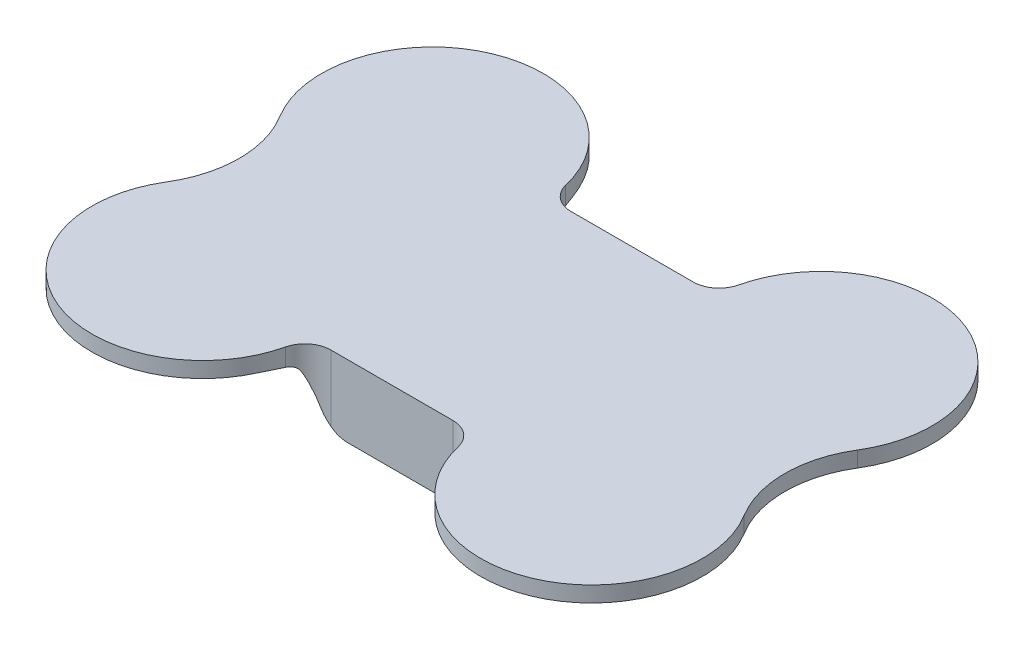
SolidWorks part; units mm, degrees
material "P-FIlament 721"
ref_plane "Front Plane" through (0, 0, 0) normal (0, 0, 1) x (1, 0, 0)
ref_plane "Top Plane" through (0, 0, 0) normal (0, 1, 0) x (1, 0, 0)
ref_plane "Right Plane" through (0, 0, 0) normal (1, 0, 0) x (0, 0, -1)
sketch "Sketch2" plane through (0, 0, 0) normal (0, 1, 0) x (1, 0, 0)
  line L4 (-23.3898, -46) -> (23.3898, -46)
  line L5 (-23.3898, 46) -> (23.3898, 46)
  arc A12 (-33.1251, 53.7143) -> (-110.703, 21.7381) centre (-74.5, 44) ccw
  arc A13 (-110.703, -21.7381) -> (-33.1251, -53.7143) centre (-74.5, -44) ccw
  arc A14 (33.1251, -53.7143) -> (110.703, -21.7381) centre (74.5, -44) ccw
  arc A15 (110.703, 21.7381) -> (33.1251, 53.7143) centre (74.5, 44) ccw
  arc A16 (-23.3898, 46) -> (-33.1251, 53.7143) centre (-23.3898, 56) cw
  arc A17 (33.1251, 53.7143) -> (23.3898, 46) centre (23.3898, 56) cw
  arc A18 (23.3898, -46) -> (33.1251, -53.7143) centre (23.3898, -56) cw
  arc A19 (-23.3898, -46) -> (-33.1251, -53.7143) centre (-23.3898, -56) ccw
  arc A20 (-110.703, -21.7381) -> (-110.703, 21.7381) centre (-146.0542, 0) ccw
  arc A21 (110.703, -21.7381) -> (110.703, 21.7381) centre (146.0542, 0) cw
  dimension "D1" = 92
  dimension "D2" = 83
  dimension "D8" = 7.7143
  dimension "D3" = 42.5
  dimension "D4" = 10
  dimension "D12" = 41.5
  dimension "D5" = 46.7796
  dimension "D6" = 88
  dimension "D7" = 88
  dimension "D9" = 7.7143
  dimension "D10" = 7.7143
  dimension "D11" = 7.7143
  dimension "D13" = 35.3512
  dimension "D14" = 46
  dimension "D15" = 74.5
extrude "Boss-Extrude1" add sketch "Sketch2" along normal blind 29
sketch "Sketch4" plane through (0, 0, 0) normal (0, 0, 1) x (1, 0, 0)
  line L0 (-31.1057, 19.8143) -> (-26.4328, 7.8143)
  line L1 (26.4328, 7.8143) -> (31.1057, 19.8143)
  line L2 (-17.1144, 1.443) -> (17.1144, 1.443)
  line L3 (117, 23) -> (35.7649, 23)
  line L4 (117, 0) -> (117, 29) construction
  line L5 (117, 29) -> (33.1251, 29) construction
  line L7 (-117, 23) -> (-35.7649, 23)
  line L8 (-117, 29) -> (-117, 0) construction
  line L9 (-33.1251, 29) -> (-117, 29) construction
  arc A0 (26.4328, 7.8143) -> (17.1144, 1.443) centre (17.1144, 11.443) cw
  arc A1 (-17.1144, 1.443) -> (-26.4328, 7.8143) centre (-17.1144, 11.443) cw
  arc A2 (-35.7649, 23) -> (-31.1057, 19.8143) centre (-35.7649, 18) cw
  arc A3 (35.7649, 23) -> (31.1057, 19.8143) centre (35.7649, 18) ccw
  point P20 (23.3898, 0)
  point P23 (-23.3898, 0)
  dimension "D2" = 10
  dimension "D4" = 5
  dimension "D5" = 5
  dimension "D8" = 34.2288
  dimension "D1" = 6
  dimension "D3" = 6
  dimension "D6" = 12
  dimension "D7" = 12
  dimension "D9" = 1.443
  dimension "D10" = 81.2351
  dimension "D11" = 81.2351
extrude "Cut-Extrude3" cut sketch "Sketch4" against normal through all and the other way through all flip side to cut
